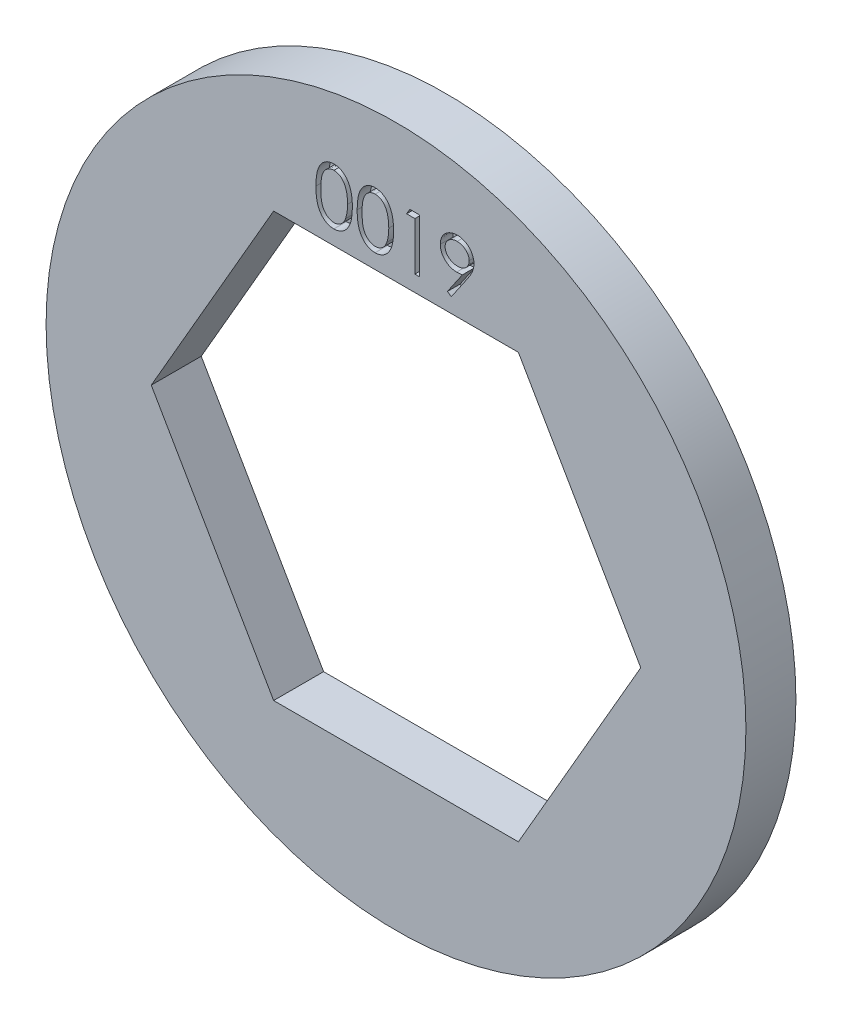
SolidWorks part; units mm, degrees
material "Nylon 101"
ref_plane "Front Plane" through (0, 0, 0) normal (0, 0, 1) x (1, 0, 0)
ref_plane "Top Plane" through (0, 0, 0) normal (0, 1, 0) x (1, 0, 0)
ref_plane "Right Plane" through (0, 0, 0) normal (1, 0, 0) x (0, 0, -1)
sketch "Sketch1" plane through (0, 0, 0) normal (0, 0, 1) x (1, 0, 0)
  line L1 (7.7723, 0) -> (3.8861, 6.731)
  line L2 (3.8861, 6.731) -> (-3.8861, 6.731)
  line L3 (-3.8861, 6.731) -> (-7.7723, 0)
  line L4 (-7.7723, 0) -> (-3.8861, -6.731)
  line L5 (-3.8861, -6.731) -> (3.8861, -6.731)
  line L6 (3.8861, -6.731) -> (7.7723, 0)
  circle A0 centre (0, 0) radius 11.1125
  circle A1 centre (0, 0) radius 6.731 construction
  dimension "D1" = 22.225
  dimension "D2" = 13.462
extrude "Boss-Extrude1" add sketch "Sketch1" along normal blind 1.5875
sketch "Sketch2" plane through (0, 0, 1.5875) normal (0, 0, 1) x (1, 0, 0)
  line L0 (-2.6079, 7.239) -> (2.9197, 7.239) construction
  line L1 (3.8861, 6.731) -> (-3.8861, 6.731) construction
  text T0 "0019" font "Century Gothic" height 1.7018
  dimension "D1" = 0.508
extrude "Cut-Extrude1" cut sketch "Sketch2" against normal blind 0.4
